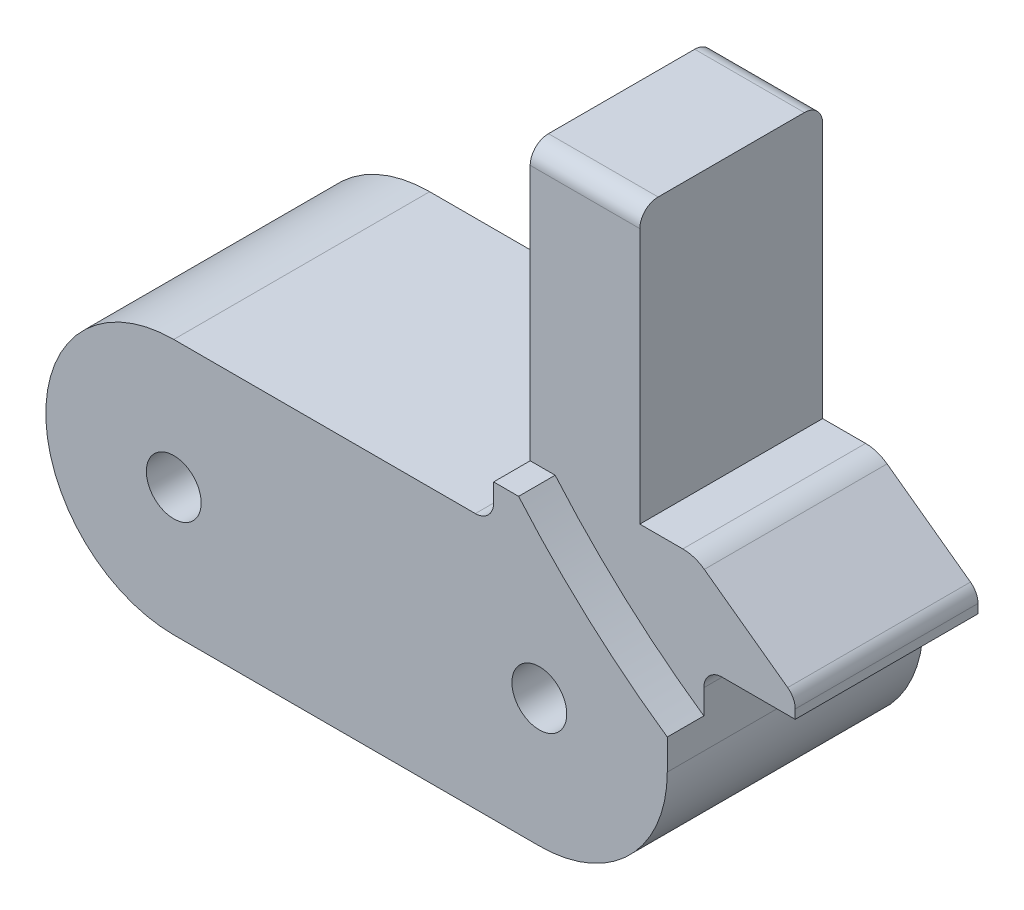
SolidWorks part; units mm, degrees
ref_plane "前视基准面" through (0, 0, 0) normal (0, 0, 1) x (1, 0, 0)
ref_plane "上视基准面" through (0, 0, 0) normal (0, 1, 0) x (1, 0, 0)
ref_plane "右视基准面" through (0, 0, 0) normal (1, 0, 0) x (0, 0, -1)
sketch "草图1" plane through (0, 0, 0) normal (0, 0, 1) x (1, 0, 0)
  line L0 (-20, 7) -> (-2.5, 7)
  line L1 (-20, -7) -> (0, -7)
  line L2 (-2.5, 7) -> (-2.5, 26)
  line L3 (-2.5, 26) -> (3.5, 26)
  line L4 (3.5, 26) -> (3.5, 9)
  line L5 (3.5, 9) -> (6.5, 9)
  line L6 (7, 4) -> (12, 4)
  line L7 (7, 0) -> (7, 4)
  line L8 (12, 4) -> (12, 5)
  line L9 (6.5, 9) -> (12, 5)
  circle A0 centre (0, 0) radius 1.5
  circle A1 centre (-20, 0) radius 1.5
  circle A2 centre (-20, 0) radius 7
  circle A3 centre (0, 0) radius 7
  dimension "D1" = 3
  dimension "D2" = 3
  dimension "D4" = 3.5
  dimension "D10" = 14
  dimension "D11" = 14
  dimension "D3" = 20
  dimension "D5" = 6
  dimension "D6" = 17
  dimension "D7" = 3
  dimension "D8" = 5
  dimension "D9" = 1
  dimension "D12" = 5
extrude "凸台-拉伸1" add sketch "草图1" along normal blind 14
fillet "圆角2" radius 1 2 edges at (7, 4, 7) (-2.5, 7, 7)
fillet "圆角4" radius 2 1 edges at (6.5, 9, 7)
fillet "圆角5" radius 1 1 edges at (12, 5, 7)
sketch "草图2" plane through (3.5, 0, 0) normal (1, 0, 0) x (0, 0, -1)
  line L0 (-7, 28.2067) -> (-7, 1.6741) construction
  line L1 (-12, 9) -> (-14, 9)
  line L2 (-14, 9) -> (0, 9) construction
  line L3 (-14, 9) -> (-14, 26)
  line L4 (-14, 26) -> (0, 26)
  line L5 (-12, 9) -> (-12, 24)
  line L6 (-12, 24) -> (-2, 24)
  line L7 (-2, 9) -> (0, 9)
  line L8 (-2, 9) -> (-2, 24)
  line L9 (0, 9) -> (0, 26)
  point P10 (-7, 24)
  point P16 (-7, 26)
  dimension "D1" = 2
  dimension "D2" = 10
extrude "切除-拉伸1" cut sketch "草图2" against normal blind 10
fillet "圆角6" radius 1 2 edges at (0.5, 24, 2) (0.5, 24, 12)
sketch "草图4" plane through (0, 0, 14) normal (0, 0, 1) x (1, 0, 0)
  line L1 (59.5, 65) -> (3.5, 65)
  line L2 (59.5, 65) -> (59.5, 9)
  line L3 (59.5, 9) -> (3.5, 9)
  line L4 (3.5, 65) -> (3.5, 9)
  line L5 (31.5, 9) -> (31.5, 65) construction
  line L6 (59.5, 37) -> (3.5, 37) construction
  circle A0 centre (31.5, 37) radius 43
  point P0 (31.5, 37)
  dimension "D1" = 56
  dimension "D2" = 56
extrude "切除-拉伸2" cut sketch "草图4" against normal blind 2
ref_plane "基准面1" through (0, 0, 7) normal (0, 0, 1) x (1, 0, 0)
mirror "镜向1" about plane through (0, 0, 7) normal (0, 0, 1) of "切除-拉伸2"
